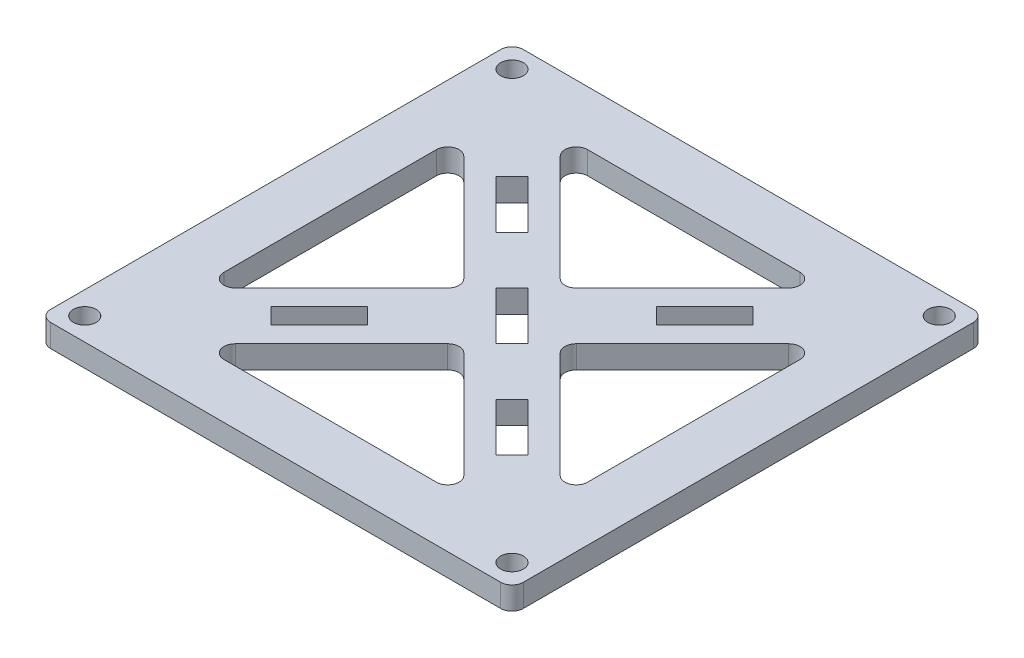
SolidWorks part; units mm, degrees
ref_plane "Front Plane" through (0, 0, 0) normal (0, 0, 1) x (1, 0, 0)
ref_plane "Top Plane" through (0, 0, 0) normal (0, 1, 0) x (1, 0, 0)
ref_plane "Right Plane" through (0, 0, 0) normal (1, 0, 0) x (0, 0, -1)
sketch "Sketch1" plane through (0, 0, 0) normal (0, 1, 0) x (1, 0, 0)
  line L0 (-14.8322, 25.4) -> (14.8322, 25.4)
  line L5 (15.7154, -17.9605) -> (17.9605, -15.7154)
  line L6 (-14.8322, -25.4) -> (14.8322, -25.4)
  line L7 (-31.4325, 33.02) -> (31.4325, 33.02)
  line L9 (33.02, -31.4325) -> (33.02, 31.4325)
  line L11 (8.9803, -11.2253) -> (11.2253, -8.9803)
  line L12 (-31.4325, -33.02) -> (31.4325, -33.02)
  line L13 (-33.02, -31.4325) -> (-33.02, 31.4325)
  line L14 (-15.7154, 17.9605) -> (-8.9803, 11.2253)
  line L15 (-17.9605, 15.7154) -> (-11.2253, 8.9803)
  line L16 (-17.9605, -15.7154) -> (-11.2253, -8.9803)
  line L17 (-15.7154, -17.9605) -> (-8.9803, -11.2253)
  line L18 (-15.9548, 22.69) -> (-1.1225, 7.8577)
  line L19 (-22.69, 15.9548) -> (-7.8577, 1.1225)
  line L20 (-22.69, -15.9548) -> (-7.8577, -1.1225)
  line L21 (-15.9548, -22.69) -> (-1.1225, -7.8577)
  line L22 (-4.4901, 2.2451) -> (-2.2451, 4.4901)
  line L23 (8.9803, 11.2253) -> (15.7154, 17.9605)
  line L25 (25.4, -14.8322) -> (25.4, 14.8322)
  line L26 (11.2253, 8.9803) -> (17.9605, 15.7154)
  line L27 (2.2451, -4.4901) -> (4.4901, -2.2451)
  line L28 (-11.2253, -8.9803) -> (-8.9803, -11.2253)
  line L29 (7.8577, 1.1225) -> (22.69, 15.9548)
  line L32 (1.1225, 7.8577) -> (15.9548, 22.69)
  line L33 (11.2253, -8.9803) -> (17.9605, -15.7154)
  line L35 (-2.2451, 4.4901) -> (4.4901, -2.2451)
  line L36 (-4.4901, 2.2451) -> (2.2451, -4.4901)
  line L37 (-11.2253, 8.9803) -> (-8.9803, 11.2253)
  line L38 (-17.9605, 15.7154) -> (-15.7154, 17.9605)
  line L39 (8.9803, -11.2253) -> (15.7154, -17.9605)
  line L40 (-32.1352, 11.9296) -> (11.9296, -32.1352) construction
  line L41 (-17.9605, -15.7154) -> (-15.7154, -17.9605)
  line L44 (15.7154, 17.9605) -> (17.9605, 15.7154)
  line L45 (-38.8704, 5.1944) -> (5.1944, -38.8704) construction
  line L46 (8.9803, 11.2253) -> (11.2253, 8.9803)
  line L47 (7.8577, -1.1225) -> (22.69, -15.9548)
  line L48 (1.1225, -7.8577) -> (15.9548, -22.69)
  line L49 (-25.4, 18.6648) -> (18.6648, -25.4) construction
  line L50 (-25.4, -14.8322) -> (-25.4, 14.8322)
  circle A0 centre (-29.845, 29.845) radius 1.5875
  circle A1 centre (29.845, 29.845) radius 1.5875
  circle A2 centre (29.845, -29.845) radius 1.5875
  circle A3 centre (-29.845, -29.845) radius 1.5875
  arc A4 (-22.69, 15.9548) -> (-25.4, 14.8322) centre (-23.8125, 14.8322) ccw
  arc A5 (-7.8577, -1.1225) -> (-7.8577, 1.1225) centre (-8.9803, 0) ccw
  arc A6 (1.1225, 7.8577) -> (-1.1225, 7.8577) centre (0, 8.9803) cw
  arc A7 (-15.9548, 22.69) -> (-14.8322, 25.4) centre (-14.8322, 23.8125) cw
  arc A8 (15.9548, 22.69) -> (14.8322, 25.4) centre (14.8322, 23.8125) ccw
  arc A9 (22.69, 15.9548) -> (25.4, 14.8322) centre (23.8125, 14.8322) cw
  arc A10 (7.8577, 1.1225) -> (7.8577, -1.1225) centre (8.9803, 0) ccw
  arc A11 (22.69, -15.9548) -> (25.4, -14.8322) centre (23.8125, -14.8322) ccw
  arc A12 (15.9548, -22.69) -> (14.8322, -25.4) centre (14.8322, -23.8125) cw
  arc A13 (-1.1225, -7.8577) -> (1.1225, -7.8577) centre (0, -8.9803) cw
  arc A14 (-22.69, -15.9548) -> (-25.4, -14.8322) centre (-23.8125, -14.8322) cw
  arc A15 (-15.9548, -22.69) -> (-14.8322, -25.4) centre (-14.8322, -23.8125) ccw
  arc A16 (-31.4325, -33.02) -> (-33.02, -31.4325) centre (-31.4325, -31.4325) cw
  arc A17 (33.02, -31.4325) -> (31.4325, -33.02) centre (31.4325, -31.4325) cw
  arc A18 (31.4325, 33.02) -> (33.02, 31.4325) centre (31.4325, 31.4325) cw
  arc A19 (-31.4325, 33.02) -> (-33.02, 31.4325) centre (-31.4325, 31.4325) ccw
  point P63 (6.7352, 0)
  point P71 (0, -6.7352)
extrude "Boss-Extrude1" add sketch "Sketch1" along normal blind 3.175
